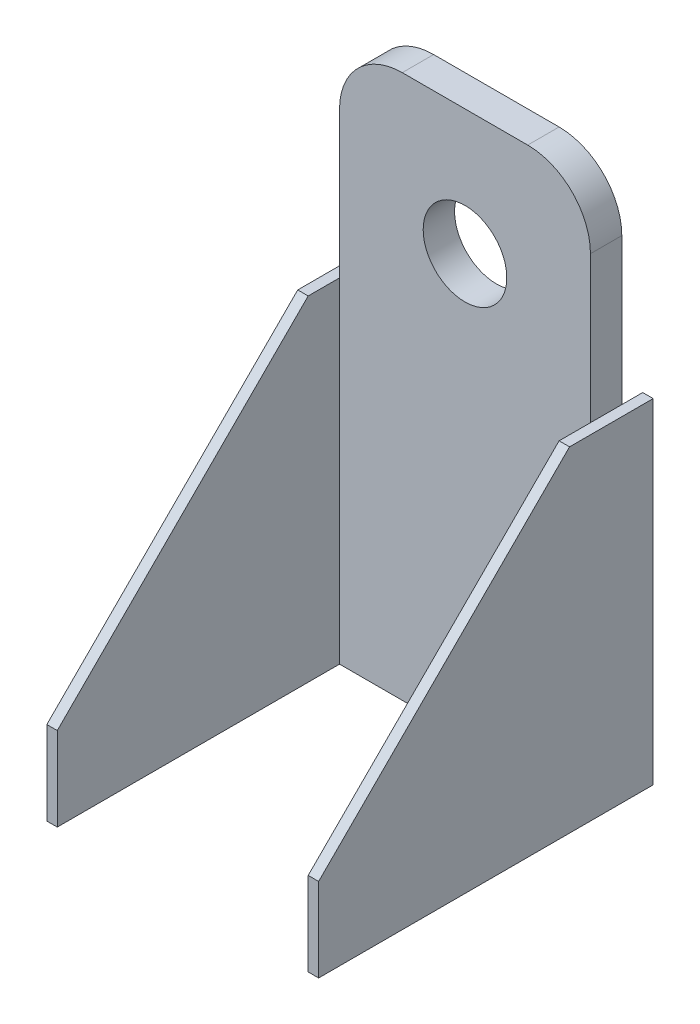
SolidWorks part; units mm, degrees
ref_plane "Front Plane" through (0, 0, 0) normal (0, 0, 1) x (1, 0, 0)
ref_plane "Top Plane" through (0, 0, 0) normal (0, 1, 0) x (1, 0, 0)
ref_plane "Right Plane" through (0, 0, 0) normal (1, 0, 0) x (0, 0, -1)
sketch "Sketch2" plane through (0, 0, 0) normal (0, 0, 1) x (1, 0, 0)
  line L1 (-76.2, 76.2) -> (76.2, 76.2)
  line L2 (-76.2, 76.2) -> (-76.2, -254)
  line L3 (-76.2, -254) -> (76.2, -254)
  line L4 (76.2, 76.2) -> (76.2, -254)
  point P4 (0, 76.2)
  dimension "D1" = 152.4
  dimension "D2" = 76.2
  dimension "D3" = 254
extrude "Boss-Extrude1" add sketch "Sketch2" along normal blind 19.05
sketch "Sketch5" plane through (0, 0, 0) normal (0, 0, 1) x (1, 0, 0)
  circle A0 centre (0, 0) radius 25.4
  dimension "D1" = 50.8
extrude "Cut-Extrude1" cut sketch "Sketch5" along normal through all
fillet "Fillet1" radius 38.1 2 edges at (76.2, 76.2, 9.525) (-76.2, 76.2, 9.525)
sketch "Sketch3" plane through (76.2, 0, 0) normal (1, 0, 0) x (0, 0, -1)
  line L0 (12.7, -50.8) -> (12.7, -254)
  line L1 (12.7, -254) -> (-190.5, -254)
  line L2 (-190.5, -254) -> (-190.5, -203.2)
  line L3 (-190.5, -203.2) -> (-38.1, -50.8)
  line L4 (-38.1, -50.8) -> (12.7, -50.8)
  dimension "D1" = 203.2
  dimension "D2" = 12.7
  dimension "D3" = 50.8
  dimension "D4" = 50.8
  dimension "D5" = 203.2
  dimension "D6" = 254
extrude "Boss-Extrude2" add sketch "Sketch3" along normal blind 6.35
mirror "Mirror1" about plane through (0, 0, 0) normal (1, 0, 0) of "Boss-Extrude2"
sketch "Sketch4" plane through (0, 0, 0) normal (0, 0, 1) x (1, 0, 0)
  circle A0 centre (0, 0) radius 254
  dimension "D1" = 508
